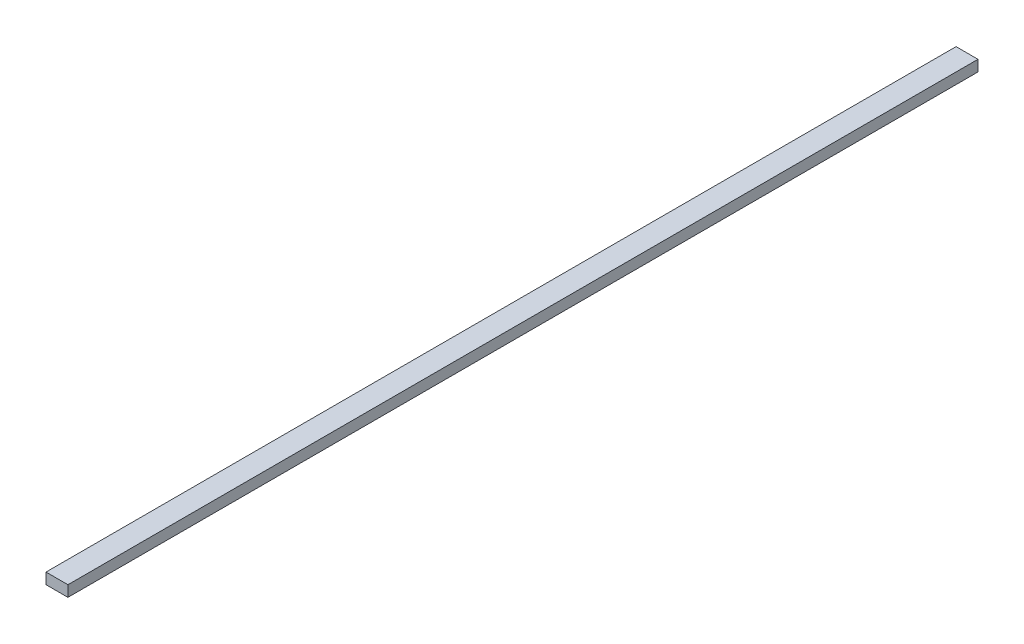
SolidWorks part; units mm, degrees
ref_plane "Front Plane" through (0, 0, 0) normal (0, 0, 1) x (1, 0, 0)
ref_plane "Top Plane" through (0, 0, 0) normal (0, 1, 0) x (1, 0, 0)
ref_plane "Right Plane" through (0, 0, 0) normal (1, 0, 0) x (0, 0, -1)
sketch "Sketch1" plane through (0, 0, 0) normal (0, 0, 1) x (1, 0, 0)
  line L1 (6.35, -3.175) -> (-6.35, -3.175)
  line L2 (6.35, -3.175) -> (6.35, 3.175)
  line L3 (6.35, 3.175) -> (-6.35, 3.175)
  line L4 (-6.35, -3.175) -> (-6.35, 3.175)
  line L5 (6.35, -3.175) -> (-6.35, 3.175) construction
  line L6 (6.35, 3.175) -> (-6.35, -3.175) construction
  point P0 (0, 0)
  dimension "D1" = 6.35
  dimension "D2" = 12.7
extrude "Boss-Extrude1" add sketch "Sketch1" along normal blind 527.05
